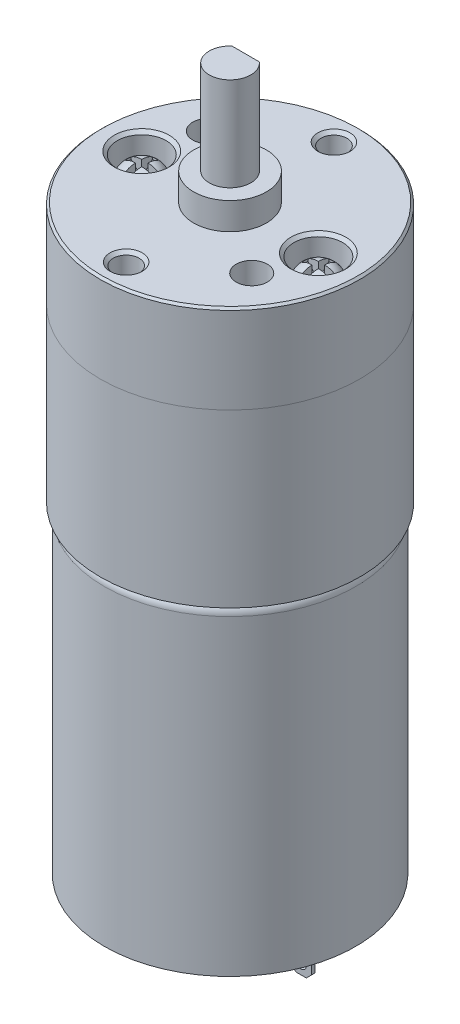
SolidWorks part; units mm, degrees
material "1060 Alloy"
ref_plane "Front Plane" through (0, 0, 0) normal (0, 0, 1) x (1, 0, 0)
ref_plane "Top Plane" through (0, 0, 0) normal (0, 1, 0) x (1, 0, 0)
ref_plane "Right Plane" through (0, 0, 0) normal (1, 0, 0) x (0, 0, -1)
sketch "Sketch1" plane through (0, 0, 0) normal (0, 1, 0) x (1, 0, 0)
  circle A0 centre (0, 0) radius 12.1
  dimension "D1" = 24.2
extrude "Boss-Extrude1" add sketch "Sketch1" along normal blind 31
fillet "Fillet1" radius 1 1 edges at (0, 31, 12.1)
sketch "Sketch2" plane through (0, 31, 0) normal (0, 1, 0) x (1, 0, 0)
  circle A0 centre (0, 0) radius 12.5
  dimension "D1" = 25
extrude "Boss-Extrude2" add sketch "Sketch2" along normal blind 25 separate body
sketch "Sketch3" plane through (0, 0, 0) normal (1, 0, 0) x (0, 0, -1)
  line L0 (-22.9269, 47.5) -> (24.9569, 47.5)
  line L1 (12.5, 56) -> (-12.5, 56) construction
  dimension "D1" = 8.5
split line "Split Line1"
chamfer "Chamfer1" distance 0.2 angle 45 1 edges at (0, 56, 12.5)
sketch "Sketch4" plane through (0, 0, 0) normal (0, -1, 0) x (1, 0, 0)
  circle A0 centre (0, 0) radius 11.7
  dimension "D1" = 23.4
extrude "Cut-Extrude1" cut sketch "Sketch4" against normal blind 0.9
sketch "Sketch5" plane through (0, 0.9, 0) normal (0, -1, 0) x (1, 0, 0)
  circle A0 centre (0, 0) radius 3.25
  dimension "D1" = 6.5
extrude "Boss-Extrude3" add sketch "Sketch5" along normal blind 2.2
fillet "Fillet2" radius 1 1 edges at (0, -1.3, -3.25)
sketch "Sketch6" plane through (0, 0.9, 0) normal (0, -1, 0) x (1, 0, 0)
  line L0 (-9, 1.5) -> (-9, -1.5) construction
  line L1 (-7.47, 1.5) -> (-7.47, -1.5)
  line L2 (-10.53, 1.5) -> (-10.53, -1.5)
  line L3 (0, 0) -> (-16.4723, 0) construction
  line L4 (0, 0) -> (0, -6.2371) construction
  line L5 (9, 1.5) -> (9, -1.5) construction
  line L6 (7.47, 1.5) -> (7.47, -1.5)
  line L7 (10.53, 1.5) -> (10.53, -1.5)
  arc A0 (-7.47, 1.5) -> (-10.53, 1.5) centre (-9, 1.5) ccw
  arc A1 (-10.53, -1.5) -> (-7.47, -1.5) centre (-9, -1.5) ccw
  arc A2 (7.47, 1.5) -> (10.53, 1.5) centre (9, 1.5) cw
  arc A3 (10.53, -1.5) -> (7.47, -1.5) centre (9, -1.5) cw
  point P2 (-9, 0)
  point P13 (9, 0)
  dimension "D2" = 1.53
  dimension "D1" = 3
  dimension "D3" = 9
split line "Split Line2"
sketch "Sketch7" plane through (0, 0.9, 0) normal (0, -1, 0) x (1, 0, 0)
  line L1 (-7.661, -1.71) -> (-9.661, -1.71)
  line L2 (-7.661, -1.71) -> (-7.661, -1.36)
  line L3 (-7.661, -1.36) -> (-9.661, -1.36)
  line L4 (-9.661, -1.71) -> (-9.661, -1.36)
  line L5 (-7.661, -1.71) -> (-9.661, -1.36) construction
  line L6 (-7.661, -1.36) -> (-9.661, -1.71) construction
  line L7 (9.7495, 1.5573) -> (7.7495, 1.5573)
  line L8 (9.7495, 1.5573) -> (9.7495, 1.9073)
  line L9 (9.7495, 1.9073) -> (7.7495, 1.9073)
  line L10 (7.7495, 1.5573) -> (7.7495, 1.9073)
  line L11 (9.7495, 1.5573) -> (7.7495, 1.9073) construction
  line L12 (9.7495, 1.9073) -> (7.7495, 1.5573) construction
  point P0 (-8.661, -1.535)
  point P5 (8.7495, 1.7323)
  dimension "D1" = 2
  dimension "D2" = 0.35
  dimension "D3" = 0.35
  dimension "D4" = 2
extrude "Boss-Extrude4" add sketch "Sketch7" along normal blind 4
chamfer "Chamfer2" distance 0.5 angle 45 4 edges at (-7.661, -3.1, -1.535) (-9.661, -3.1, -1.535) (7.7495, -3.1, 1.7323) (9.7495, -3.1, 1.7323)
sketch "Sketch8" plane through (0, 0, -1.36) normal (0, 0, 1) x (1, 0, 0)
  line L0 (-8.661, -3.1) -> (-8.661, -0.3288) construction
  line L1 (-8.161, -3.1) -> (-9.161, -3.1) construction
  line L2 (8.7495, -3.1) -> (8.7495, -0.7233) construction
  line L3 (9.2495, -3.1) -> (8.2495, -3.1) construction
  circle A0 centre (-8.661, -2.1) radius 0.5
  circle A1 centre (8.7495, -2.1) radius 0.5
  dimension "D1" = 1
  dimension "D2" = 1
  dimension "D3" = 1
extrude "Cut-Extrude2" cut sketch "Sketch8" against normal blind 4 and the other way through all
sketch "Sketch9" plane through (0, 0.9, 0) normal (0, -1, 0) x (1, 0, 0)
  circle A0 centre (0, 0) radius 3.75
  circle A1 centre (0, 0) radius 4.75
  dimension "D1" = 7.5
  dimension "D2" = 9.5
extrude "Cut-Extrude3" cut sketch "Sketch9" against normal blind 0.2
sketch "Sketch10" plane through (0, 1.1, 0) normal (0, -1, 0) x (1, 0, 0)
  line L0 (0, 0) -> (-5.9916, 0) construction
  line L1 (0, 0) -> (0, 6.3849) construction
  arc A0 (-3.4173, 1.5441) -> (-3.4173, -1.5441) centre (0, 0) ccw
  arc A1 (-4.3286, 1.9559) -> (-4.3286, -1.9559) centre (0, 0) ccw
  arc A2 (-3.6407, 2.1927) -> (-3.6407, -2.1927) centre (0, 0) ccw construction
  arc A3 (-3.4173, 1.5441) -> (-4.3286, 1.9559) centre (-3.873, 1.75) ccw
  arc A4 (-4.3286, -1.9559) -> (-3.4173, -1.5441) centre (-3.873, -1.75) ccw
  arc A5 (3.6407, 2.1927) -> (3.6407, -2.1927) centre (0, 0) cw construction
  arc A6 (4.3286, -1.9559) -> (3.4173, -1.5441) centre (3.873, -1.75) cw
  arc A7 (3.4173, 1.5441) -> (4.3286, 1.9559) centre (3.873, 1.75) cw
  arc A8 (4.3286, 1.9559) -> (4.3286, -1.9559) centre (0, 0) cw
  arc A9 (3.4173, 1.5441) -> (3.4173, -1.5441) centre (0, 0) cw
  dimension "D1" = 8.5
  dimension "D2" = 3.5
extrude "Cut-Extrude4" cut sketch "Sketch10" against normal blind 10
sketch "Sketch11" plane through (0, 56, 0) normal (0, 1, 0) x (1, 0, 0)
  circle A0 centre (0, 0) radius 3.5
  dimension "D1" = 7
extrude "Boss-Extrude5" add sketch "Sketch11" along normal blind 2.6 separate body
sketch "Sketch12" plane through (0, 58.6, 0) normal (0, 1, 0) x (1, 0, 0)
  circle A0 centre (0, 0) radius 2
  dimension "D1" = 4
extrude "Boss-Extrude6" add sketch "Sketch12" along normal blind 9 separate body
sketch "Sketch13" plane through (0, 67.6, 0) normal (0, 1, 0) x (1, 0, 0)
  line L1 (2.2159, 1.5) -> (-2.4569, 1.5)
  line L2 (2.2159, 1.5) -> (2.2159, 2.4927)
  line L3 (2.2159, 2.4927) -> (-2.4569, 2.4927)
  line L4 (-2.4569, 1.5) -> (-2.4569, 2.4927)
  line L5 (2.2159, 1.5) -> (-2.4569, 2.4927) construction
  line L6 (2.2159, 2.4927) -> (-2.4569, 1.5) construction
  circle A0 centre (0, 0) radius 2 construction
  circle A1 centre (0, 0) radius 3.5 construction
  point P0 (-0.1205, 1.9964)
  dimension "D1" = 1.5
extrude "Cut-Extrude5" cut sketch "Sketch13" against normal blind 8
sketch "Sketch14" plane through (0, 56, 0) normal (0, 1, 0) x (1, 0, 0)
  circle A0 centre (0, 0) radius 8.5 construction
  circle A1 centre (-8.5, 0) radius 2.35
  circle A2 centre (8.5, 0) radius 2.35
  dimension "D1" = 17
  dimension "D2" = 4.7
extrude "Cut-Extrude6" cut sketch "Sketch14" against normal blind 3
sketch "Sketch15" plane through (0, 53, 0) normal (0, 1, 0) x (1, 0, 0)
  circle A0 centre (-8.5, 0) radius 1.9544
extrude "Boss-Extrude7" add sketch "Sketch15" along normal blind 2 separate body
fillet "Fillet3" radius 1.5 1 edges at (-8.5, 55, 1.9544)
sketch "Sketch16" plane through (0, 55, 0) normal (0, 1, 0) x (1, 0, 0)
  line L1 (-8.2, -1.3175) -> (-8.8, -1.3175)
  line L2 (-8.2, -1.3175) -> (-8.2, -0.3)
  line L3 (-8.2, 1.3175) -> (-8.8, 1.3175)
  line L4 (-8.8, -1.3175) -> (-8.8, -0.3)
  line L7 (-9.8175, 0.3) -> (-8.8, 0.3)
  line L8 (-9.8175, 0.3) -> (-9.8175, -0.3)
  line L9 (-9.8175, -0.3) -> (-8.8, -0.3)
  line L10 (-7.1825, 0.3) -> (-7.1825, -0.3)
  line L16 (-8.2, -0.3) -> (-7.1825, -0.3)
  line L17 (-8.2, 0.3) -> (-7.1825, 0.3)
  line L18 (-8.8, 0.3) -> (-8.8, 1.3175)
  line L19 (-8.2, 0.3) -> (-8.2, 1.3175)
  point P0 (-8.5, 0)
  point P6 (-8.5, 0)
  dimension "D1" = 0.6
extrude "Cut-Extrude7" cut sketch "Sketch16" against normal blind 1.5
chamfer "Chamfer3" distance 1 angle 45 4 edges at (-8.5, 53.5, 1.3175) (-8.5, 53.5, -1.3175) (-7.1825, 53.5, 0) (-9.8175, 53.5, 0)
mirror "Mirror1" about plane through (0, 0, 0) normal (1, 0, 0) of bodies 116
chamfer "Chamfer4" distance 0.3 angle 45 2 edges at (8.5, 56, 2.35) (-8.5, 56, 2.35)
sketch "Sketch17" plane through (0, 56, 0) normal (0, 1, 0) x (1, 0, 0)
  circle A0 centre (0, 0) radius 10 construction
  circle A1 centre (0, 10) radius 1.25
  circle A2 centre (0, -10) radius 1.25
  dimension "D1" = 20
  dimension "D2" = 2.5
extrude "Cut-Extrude8" cut sketch "Sketch17" against normal blind 6
chamfer "Chamfer5" distance 0.3 angle 45 2 edges at (0, 56, 11.25) (0, 56, -8.75)
sketch "Sketch18" plane through (0, 56, 0) normal (0, 1, 0) x (1, 0, 0)
  line L0 (6.9628, -4.8754) -> (-6.9628, 4.8754) construction
  line L1 (0, 0) -> (-8.5, 0) construction
  circle A0 centre (0, 0) radius 8.5 construction
  circle A1 centre (-6.9628, 4.8754) radius 1.5
  circle A2 centre (6.9628, -4.8754) radius 1.5
  point P7 (-8.5, 0)
  dimension "D1" = 17
  dimension "D2" = 3
  dimension "D3" = 35
extrude "Cut-Extrude9" cut sketch "Sketch18" against normal blind 5
